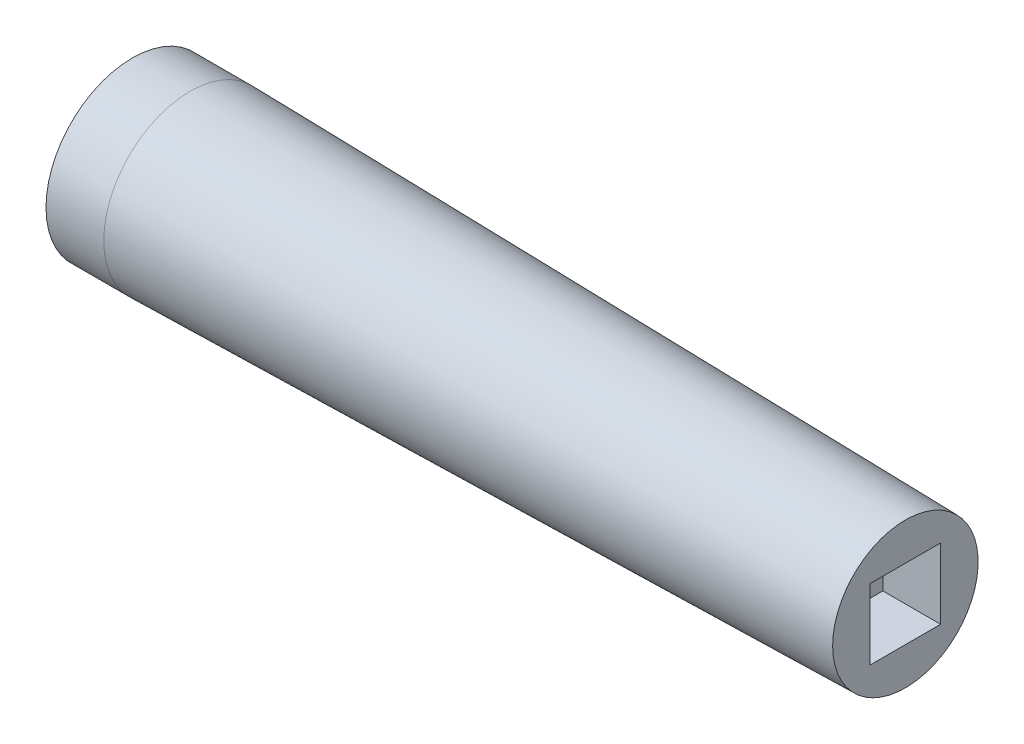
SolidWorks part; units mm, degrees
ref_plane "Front Plane" through (0, 0, 0) normal (0, 0, 1) x (1, 0, 0)
ref_plane "Top Plane" through (0, 0, 0) normal (0, 1, 0) x (1, 0, 0)
ref_plane "Right Plane" through (0, 0, 0) normal (1, 0, 0) x (0, 0, -1)
sketch "Sketch1" plane through (0, 0, 0) normal (0, 0, 1) x (1, 0, 0)
  line L0 (0, 0) -> (170, 0)
  line L1 (170, 0) -> (170, 16)
  line L2 (170, 16) -> (12.7, 19)
  line L3 (12.7, 19) -> (0, 19)
  line L4 (0, 19) -> (0, 0)
  dimension "D1" = 157.3
  dimension "D2" = 12.7
  dimension "D3" = 16
  dimension "D4" = 19
revolve "Revolve1" add sketch "Sketch1" angle 360 about L0
sketch "Sketch2" plane through (170, 0, 0) normal (1, 0, 0) x (0, 0, -1)
  line L1 (-7.75, 7.75) -> (7.75, 7.75)
  line L2 (-7.75, 7.75) -> (-7.75, -7.75)
  line L3 (-7.75, -7.75) -> (7.75, -7.75)
  line L4 (7.75, 7.75) -> (7.75, -7.75)
  line L5 (-7.75, 7.75) -> (7.75, -7.75) construction
  line L6 (-7.75, -7.75) -> (7.75, 7.75) construction
  point P0 (0, 0)
  dimension "D1" = 15.5
extrude "Cut-Extrude1" cut sketch "Sketch2" against normal blind 12.7 and the other way through all
